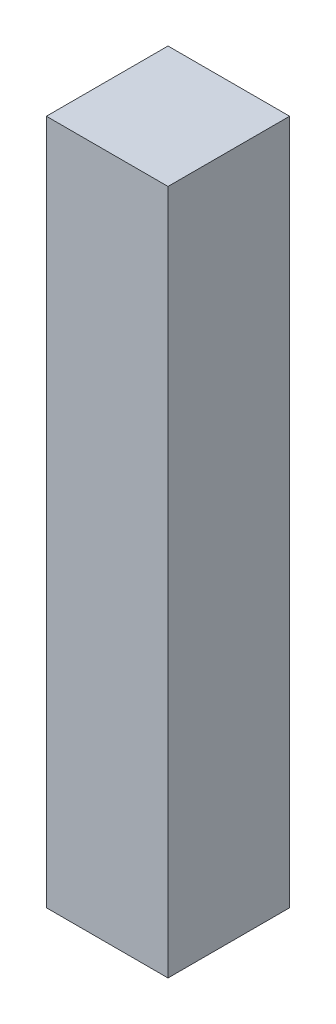
SolidWorks part; units mm, degrees
material "ﾁｰｸ材"
ref_plane "正面" through (0, 0, 0) normal (0, 0, 1) x (1, 0, 0)
ref_plane "平面" through (0, 0, 0) normal (0, 1, 0) x (1, 0, 0)
ref_plane "右側面" through (0, 0, 0) normal (1, 0, 0) x (0, 0, -1)
sketch "ｽｹｯﾁ1" plane through (0, 0, 0) normal (0, 0, 1) x (1, 0, 0)
  line L1 (2.75, 15.5) -> (-2.75, 15.5)
  line L2 (2.75, 15.5) -> (2.75, -15.5)
  line L3 (2.75, -15.5) -> (-2.75, -15.5)
  line L4 (-2.75, 15.5) -> (-2.75, -15.5)
  line L5 (2.75, 15.5) -> (-2.75, -15.5) construction
  line L6 (2.75, -15.5) -> (-2.75, 15.5) construction
  point P0 (0, 0)
  dimension "D1" = 31
  dimension "D2" = 5.5
extrude "ﾎﾞｽ - 押し出し1" add sketch "ｽｹｯﾁ1" along normal blind 5.5
